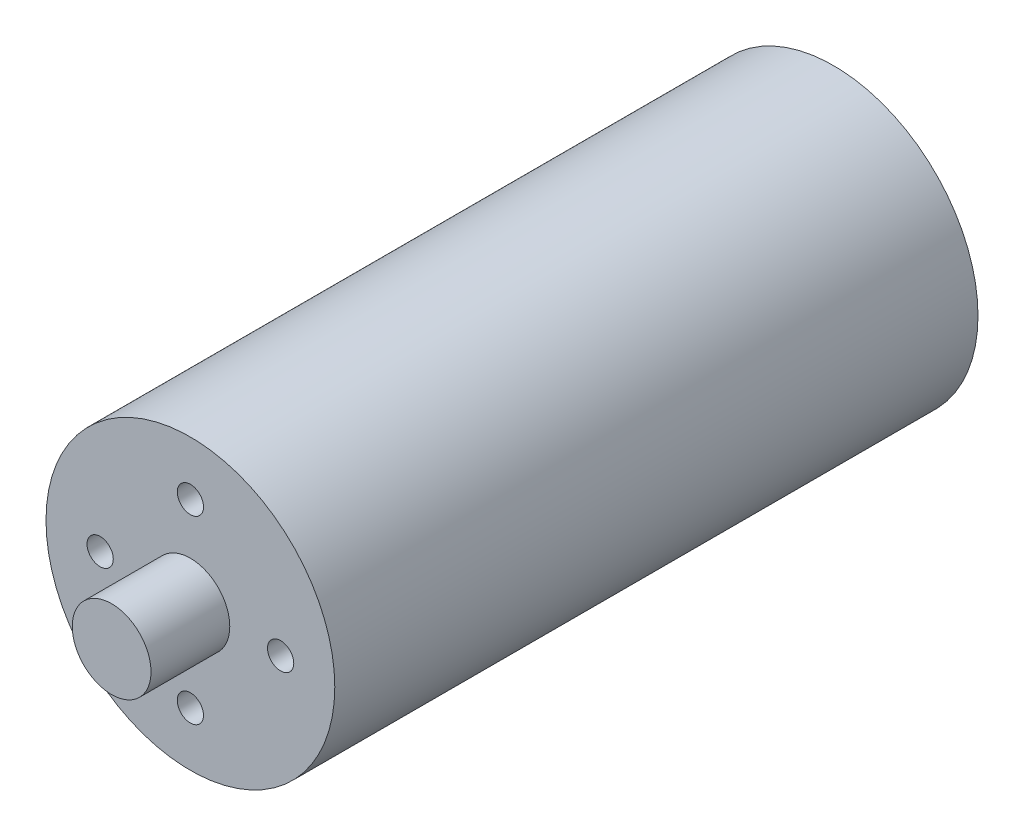
SolidWorks part; units mm, degrees
ref_plane "Front Plane" through (0, 0, 0) normal (0, 0, 1) x (1, 0, 0)
ref_plane "Top Plane" through (0, 0, 0) normal (0, 1, 0) x (1, 0, 0)
ref_plane "Right Plane" through (0, 0, 0) normal (1, 0, 0) x (0, 0, -1)
sketch "Sketch1" plane through (0, 0, 0) normal (0, 0, 1) x (1, 0, 0)
  circle A0 centre (0, 0) radius 11
  dimension "D1" = 22
extrude "Boss-Extrude1" add sketch "Sketch1" along normal blind 49
sketch "Sketch2" plane through (0, 0, 49) normal (0, 0, 1) x (1, 0, 0)
  circle A0 centre (6.875, 0) radius 1
  circle A1 centre (0, 0) radius 6.875 construction
  circle A2 centre (0, -6.875) radius 1
  circle A3 centre (-6.875, 0) radius 1
  circle A4 centre (0, 6.875) radius 1
  dimension "D1" = 2
  dimension "D2" = 13.75
  dimension "D3" = 4
extrude "Cut-Extrude1" cut sketch "Sketch2" against normal blind 3
sketch "Sketch3" plane through (0, 0, 49) normal (0, 0, 1) x (1, 0, 0)
  circle A0 centre (0, 0) radius 3
  dimension "D1" = 6
extrude "Boss-Extrude2" add sketch "Sketch3" along normal blind 6
